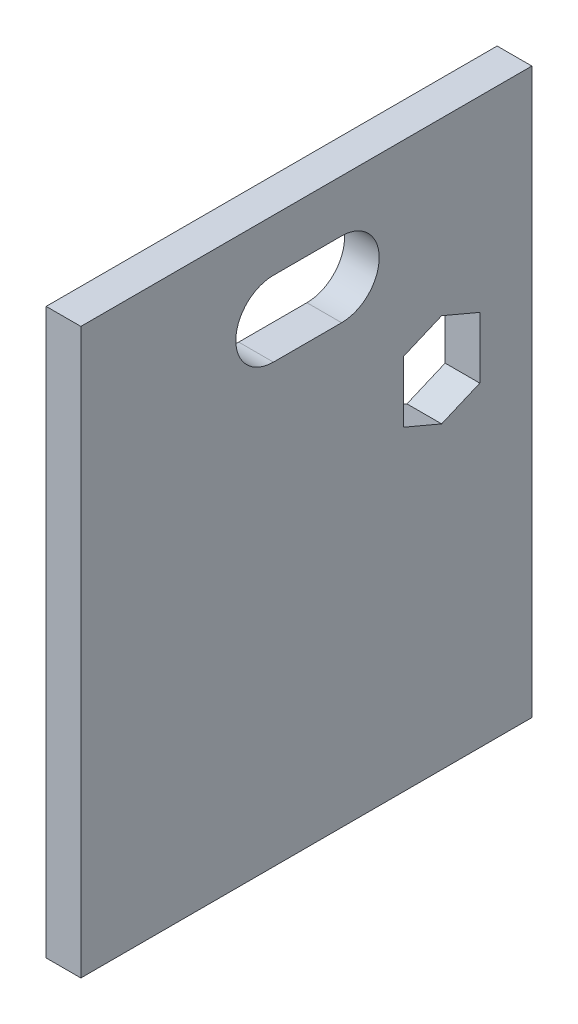
SolidWorks part; units mm, degrees
ref_plane "Alzado" through (0, 0, 0) normal (1, 0, 0) x (0, 1, 0)
ref_plane "Planta" through (0, 0, 0) normal (0, 0, 1) x (0, 1, 0)
ref_plane "Vista lateral" through (0, 0, 0) normal (0, 1, 0) x (-1, 0, 0)
sketch "Croquis1" plane through (0, 0, 0) normal (1, 0, 0) x (0, 1, 0)
  line L0 (145.4739, 128) -> (218.8517, 128) construction
  line L1 (0, 0) -> (244, 0)
  line L2 (0, 0) -> (0, 195)
  line L3 (0, 195) -> (244, 195)
  line L4 (244, 0) -> (244, 195)
  line L5 (152.2748, 66) -> (228.8741, 66) construction
  line L6 (221.5, 166.2674) -> (221.5, 66) construction
  line L7 (189, 111.75) -> (189, 82.25)
  line L8 (221.5, 111.75) -> (221.5, 82.25)
  line L9 (221.5, 111.75) -> (221.5, 82.25) construction
  line L10 (221.5, 66) -> (221.5, 42.7779) construction
  line L11 (136.5, 39) -> (163, 39) construction
  line L12 (136.5, 22.5) -> (163, 22.5)
  line L13 (136.5, 22.5) -> (136.5, 55.5)
  line L14 (136.5, 55.5) -> (163, 55.5)
  line L15 (163, 22.5) -> (163, 55.5)
  line L16 (129.5, 39) -> (170, 39) construction
  line L17 (136.5, 55.5) -> (129.5, 39)
  line L18 (129.5, 39) -> (136.5, 22.5)
  line L19 (163, 55.5) -> (170, 39)
  line L20 (170, 39) -> (163, 22.5)
  circle A0 centre (205.25, 111.75) radius 16.25
  circle A1 centre (205.25, 82.25) radius 16.25
  circle A2 centre (131.6725, 39) radius 2
  circle A3 centre (167.8275, 39) radius 2
  point P32 (0, 0)
  dimension "D3" = 32.5
  dimension "D13" = 4
  dimension "D1" = 195
  dimension "D2" = 244
  dimension "D4" = 62
  dimension "D5" = 45
  dimension "D6" = 67
  dimension "D7" = 22.5
  dimension "D8" = 55.5
  dimension "D9" = 26.5
  dimension "D10" = 81
  dimension "D11" = 7
  dimension "D12" = 7
extrude "Saliente-Extruir1" add sketch "Croquis1" along normal blind 15 contours L1 L4 L3 L2 A1 L7 A0 L8 L19 L20 L12 L18 L17 L14
